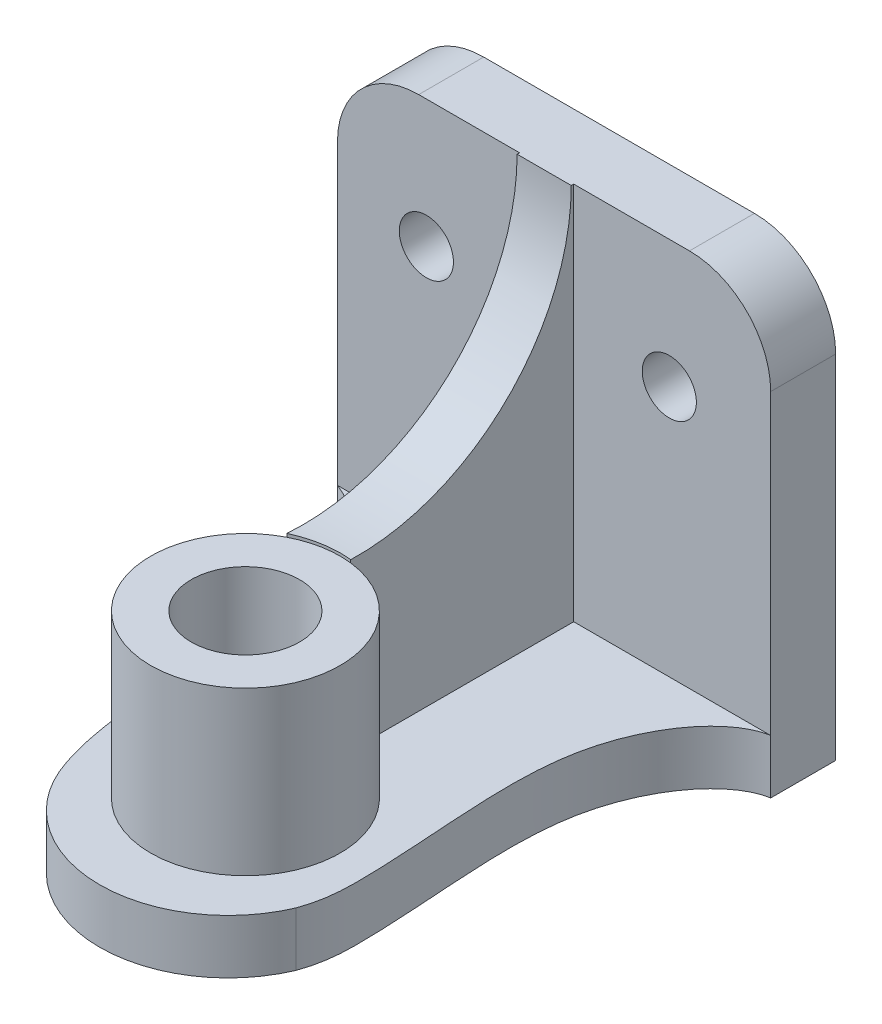
SolidWorks part; units mm, degrees
ref_plane "Front Plane" through (0, 0, 0) normal (0, 0, 1) x (1, 0, 0)
ref_plane "Top Plane" through (0, 0, 0) normal (0, 1, 0) x (1, 0, 0)
ref_plane "Right Plane" through (0, 0, 0) normal (1, 0, 0) x (0, 0, -1)
sketch "Sketch3" plane through (0, 0, 0) normal (0, 1, 0) x (1, 0, 0)
  line L0 (0, 0) -> (80, 0)
  spline S0 degree 3 poles (0, 0) (9.5688, -3.6623) (13.2338, -26.3675) (14.893, -48.2617) (19.4576, -73.3825) (29.234, -88.8426) (47.3394, -94.9785) (65.0727, -76.3559) (65.4723, -49.4998) (60.3302, -17.8205) (73.6733, -1.0046) (80, 0) knots 0 0 0 0 0.130432 0.366935 0.413509 0.549604 0.58009 0.687888 0.718701 0.857412 1 1 1 1
  point P4 (0, 0)
  point P6 (75.708, -54.9789)
  point P8 (68.7338, -53.5841)
  point P10 (64.8283, -13.6919)
  point P12 (65.1072, -52.1892)
  point P13 (64.8283, -16.2026)
  point P14 (40.1118, -71.2585)
  point P15 (35.1799, -73.8286)
  point P16 (36.5692, -79.3856)
  point P17 (65.7435, -16.5914)
  point P18 (29.6229, -75.2178)
  point P19 (0, 0)
  point P20 (39.6255, -92.1667)
  point P21 (0, 0)
  point P22 (0, 0)
  point P23 (0, 0)
  dimension "D4" = 17
  dimension "D1" = 80
  dimension "D2" = 65
  dimension "D3" = 65
extrude "Boss-Extrude2" add sketch "Sketch3" along normal blind 10
sketch "Sketch4" plane through (0, 10, 0) normal (0, 1, 0) x (1, 0, 0)
  line L0 (7.2364, -67.3387) -> (6.6336, -66.2189)
  arc A0 (20.0555, -71.3937) -> (63.7526, -71.3937) centre (41.9041, -62.0893) ccw
  spline S1 degree 3 poles (0, 0) (9.5688, -3.6623) (13.2338, -26.3675) (14.893, -48.2617) (19.4576, -73.3825) (29.234, -88.8426) (47.3394, -94.9785) (65.0727, -76.3559) (65.4723, -49.4998) (60.3302, -17.8205) (73.6733, -1.0046) (80, 0) knots 0 0 0 0 0.130432 0.366935 0.413509 0.549604 0.58009 0.687888 0.718701 0.857412 1 1 1 1 construction
extrude "Cut-Extrude-Thin1" cut sketch "Sketch4" against normal blind 10 thin
sketch "Sketch5" plane through (0, 10, 0) normal (0, 1, 0) x (1, 0, 0)
  circle A0 centre (41.5632, -58.5664) radius 17.5
  circle A1 centre (41.5632, -58.5664) radius 10
  point P3 (41.5632, -58.5664)
  dimension "D1" = 35
  dimension "D2" = 20
extrude "Boss-Extrude3" add sketch "Sketch5" along normal blind 30
sketch "Sketch7" plane through (0, 0, 0) normal (0, 0, -1) x (-1, 0, 0)
  line L1 (-80, 80) -> (0, 80)
  line L2 (-80, 80) -> (-80, 0)
  line L3 (-80, 0) -> (0, 0)
  line L4 (0, 80) -> (0, 0)
  point P5 (-80, 0)
  dimension "D1" = 80
  dimension "D2" = 80
extrude "Boss-Extrude4" add sketch "Sketch7" along normal blind 12
fillet "Fillet2" radius 15 2 edges at (80, 80, -6) (0, 80, -6)
sketch "Sketch8" plane through (0, 0, 0) normal (0, 0, 1) x (1, 0, 0)
  line L0 (15, 80) -> (65, 80) construction
  line L1 (33.6241, 80) -> (43.6241, 80)
  line L2 (33.6241, 80) -> (33.6241, 10)
  line L3 (33.6241, 10) -> (43.6241, 10)
  line L4 (43.6241, 80) -> (43.6241, 10)
  line L5 (80, 10) -> (0, 10) construction
  point P6 (43.0408, 10)
  dimension "D1" = 10
extrude "Boss-Extrude5" add sketch "Sketch8" along normal up to surface (41.1882 mm away)
sketch "Sketch9" plane through (33.6241, 0, 0) normal (-1, 0, 0) x (0, 0, 1)
  line L0 (42.9708, 80) -> (0, 80) construction
  circle A0 centre (39.9522, 80) radius 39.5
  point P3 (42.9708, 80)
  point P4 (42.9708, 80)
  point P5 (42.9708, 80)
  point P6 (39.9522, 80)
  dimension "D1" = 79
extrude "Cut-Extrude1" cut sketch "Sketch9" against normal blind 12
hole_wizard "Ø10.0mm Dowel Slot1" positions "Sketch12" profile "Sketch13" size "Ø10.0" standard "DIN" slot yes end condition through all
sketch "Sketch12" plane through (0, 0, 0) normal (0, 0, 1) x (1, 0, 0)
  point P0 (61.2792, 56.4128)
  point P2 (16.4143, 56.4128)
sketch "Sketch13" plane through (61.2792, 56.4128, 0) normal (1, 0, 0) x (0, -1, 0)
  line L0 (0, 0) -> (0, 12)
  line L1 (0, 12) -> (5, 12)
  line L2 (5, 12) -> (5, 0)
  line L5 (5, 0) -> (0, 0)
  line L11 (0, -6.35) -> (0, 107.95) construction
  dimension "Thru Hole Dia." = 10
  dimension "Thru Hole Depth" = 12
